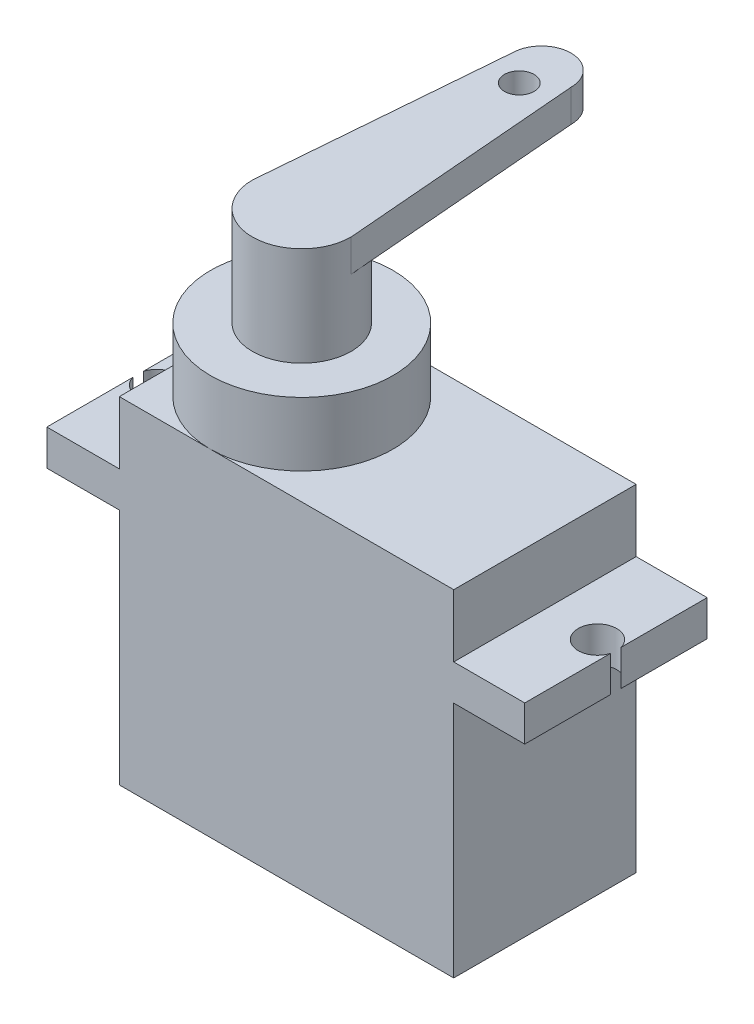
SolidWorks part; units mm, degrees
ref_plane "Front Plane" through (0, 0, 0) normal (0, 0, 1) x (1, 0, 0)
ref_plane "Top Plane" through (0, 0, 0) normal (0, 1, 0) x (1, 0, 0)
ref_plane "Right Plane" through (0, 0, 0) normal (1, 0, 0) x (0, 0, -1)
sketch "Sketch1" plane through (0, 0, 0) normal (0, 1, 0) x (1, 0, 0)
  line L1 (0, 0) -> (22.6, 0)
  line L2 (0, 0) -> (0, 12.33)
  line L3 (0, 12.33) -> (22.6, 12.33)
  line L4 (22.6, 0) -> (22.6, 12.33)
  dimension "D1" = 12.33
  dimension "D2" = 22.6
extrude "Boss-Extrude1" add sketch "Sketch1" along normal blind 16.09
sketch "Sketch2" plane through (0, 16.09, 0) normal (0, 1, 0) x (1, 0, 0)
  line L0 (0, 12.33) -> (0, 0) construction
  line L1 (-4.9, 12.33) -> (27.4, 12.33)
  line L2 (-4.9, 12.33) -> (-4.9, 0)
  line L3 (-4.9, 0) -> (27.4, 0)
  line L4 (27.4, 12.33) -> (27.4, 0)
  dimension "D1" = 32.3
  dimension "D2" = 4.9
extrude "Boss-Extrude2" add sketch "Sketch2" along normal blind 2.41
sketch "Sketch3" plane through (0, 18.5, 0) normal (0, 1, 0) x (1, 0, 0)
  line L0 (27.4, 12.33) -> (-4.9, 12.33) construction
  line L1 (0, 0) -> (22.6, 0)
  line L2 (0, 0) -> (0, 12.33)
  line L3 (0, 12.33) -> (22.6, 12.33)
  line L4 (22.6, 0) -> (22.6, 12.33)
  dimension "D1" = 22.6
extrude "Boss-Extrude3" add sketch "Sketch3" along normal blind 4.23
sketch "Sketch4" plane through (0, 22.73, 0) normal (0, 1, 0) x (1, 0, 0)
  line L0 (0, 12.33) -> (0, 0) construction
  arc A2 (0, 6.165) -> (12.33, 6.165) centre (6.165, 6.165) cw
  arc A3 (0, 6.165) -> (12.33, 6.165) centre (6.165, 6.165) ccw
  point P6 (12.33, 6.165)
  dimension "D1" = 12.33
extrude "Boss-Extrude4" add sketch "Sketch4" along normal blind 4.31
sketch "Sketch5" plane through (0, 27.04, 0) normal (0, 1, 0) x (1, 0, 0)
  circle A0 centre (6.165, 6.165) radius 3.335
extrude "Boss-Extrude5" add sketch "Sketch5" along normal blind 4.52
sketch "Sketch6" plane through (0, 31.56, 0) normal (0, 1, 0) x (1, 0, 0)
  line L2 (4.165, 22.365) -> (2.83, 6.165)
  line L4 (9.5, 6.165) -> (8.165, 22.365)
  arc A3 (2.875, 6.7109) -> (9.455, 6.7109) centre (6.165, 6.165) ccw
  arc A4 (8.165, 22.365) -> (4.165, 22.365) centre (6.165, 22.365) ccw
  circle M2 centre (6.165, 6.165) radius 3.335
extrude "Boss-Extrude8" add sketch "Sketch6" along normal blind 2.18 contours L4 L2 M2 | L4 A4 L2 M2
sketch "Sketch8" plane through (0, 18.5, 0) normal (0, 1, 0) x (1, 0, 0)
  circle A0 centre (-3.65, 6.165) radius 1.3
extrude "Cut-Extrude3" cut sketch "Sketch8" against normal blind 4 contours A0
sketch "Sketch9" plane through (0, 18.5, 0) normal (0, 1, 0) x (1, 0, 0)
  circle A0 centre (26.15, 6.165) radius 1.3
extrude "Cut-Extrude4" cut sketch "Sketch9" against normal blind 4
sketch "Sketch10" plane through (0, 33.74, 0) normal (0, 1, 0) x (1, 0, 0)
  circle A1 centre (6.165, 20.865) radius 1
extrude "Cut-Extrude5" cut sketch "Sketch10" against normal blind 10
